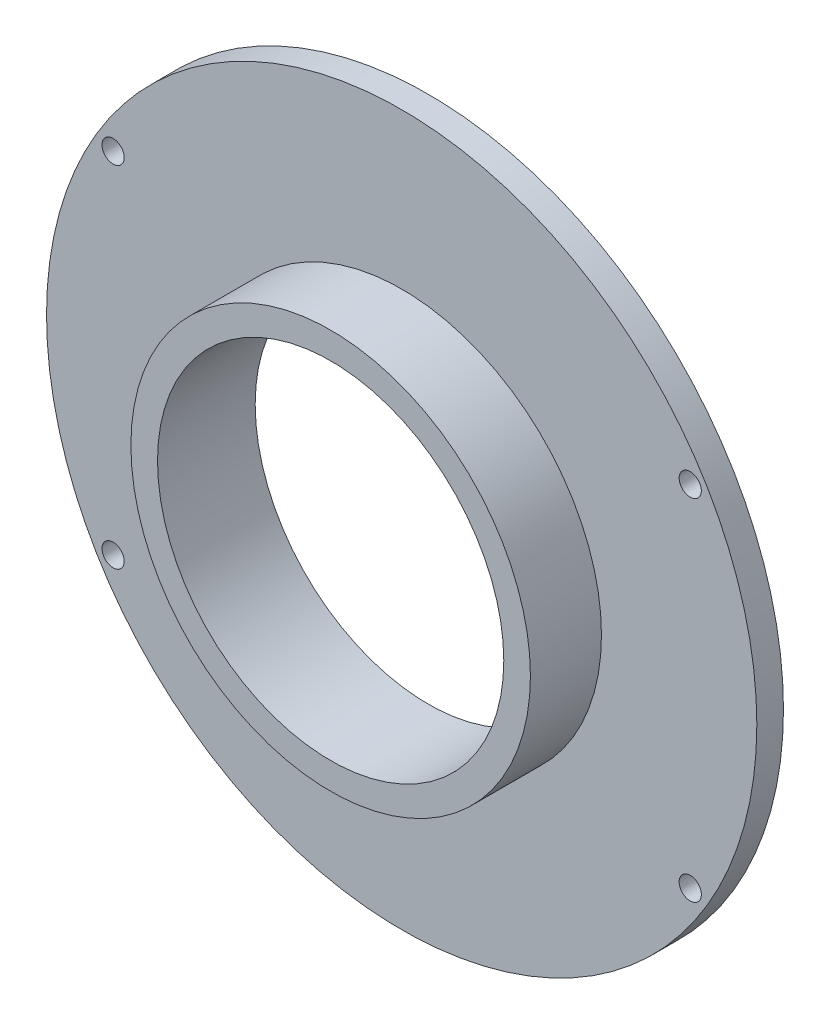
SolidWorks part; units mm, degrees
ref_plane "前视基准面" through (0, 0, 0) normal (0, 0, 1) x (1, 0, 0)
ref_plane "上视基准面" through (0, 0, 0) normal (0, 1, 0) x (1, 0, 0)
ref_plane "右视基准面" through (0, 0, 0) normal (1, 0, 0) x (0, 0, -1)
sketch "草图1" plane through (0, 0, 0) normal (0, 0, 1) x (1, 0, 0)
  circle A0 centre (0, 0) radius 22.5
  dimension "D1" = 45
extrude "凸台-拉伸1" add sketch "草图1" along normal blind 8
sketch "草图2" plane through (0, 0, 0) normal (0, 0, -1) x (-1, 0, 0)
  circle A0 centre (0, 0) radius 40
  dimension "D1" = 80
extrude "凸台-拉伸2" add sketch "草图2" along normal blind 3
sketch "草图4" plane through (0, 0, 8) normal (0, 0, 1) x (1, 0, 0)
  circle A0 centre (0, 0) radius 19.5
  dimension "D1" = 39
extrude "切除-拉伸2" cut sketch "草图4" against normal through all
sketch "草图7" plane through (0, 0, -3) normal (0, 0, -1) x (-1, 0, 0)
  line L0 (0, 38) -> (0, -38) construction
  line L1 (-38, 0) -> (38, 0) construction
  circle A0 centre (0, 0) radius 38 construction
  circle A1 centre (32.5, 19.6914) radius 1.25
  circle A2 centre (-32.5, 19.6914) radius 1.25
  circle A3 centre (32.5, -19.6914) radius 1.25
  circle A4 centre (-32.5, -19.6914) radius 1.25
  dimension "D1" = 76
  dimension "D3" = 2.5
  dimension "D2" = 32.5
extrude "切除-拉伸4" cut sketch "草图7" against normal through all
